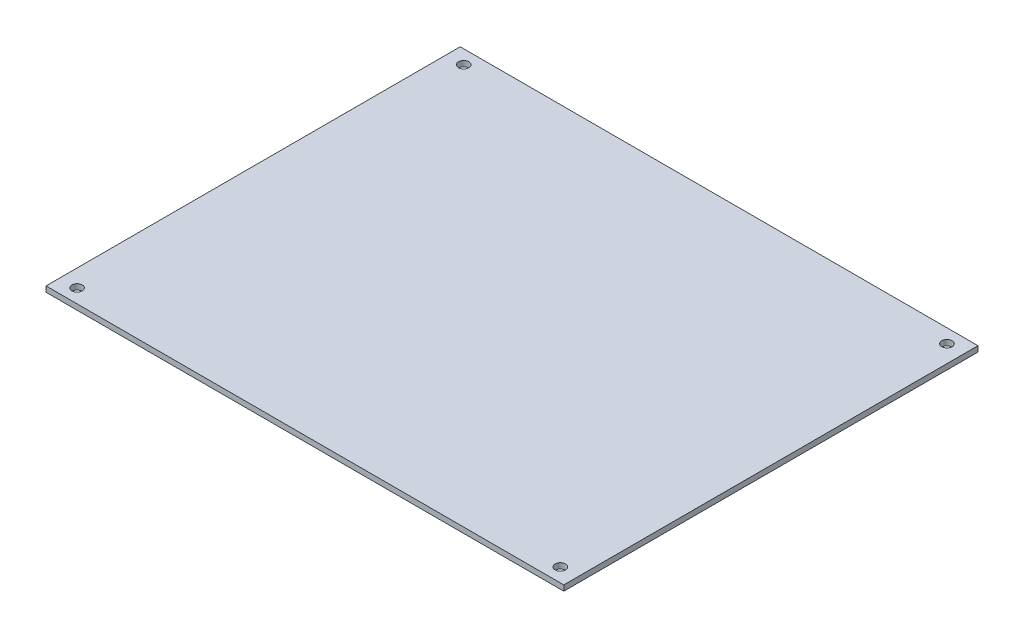
SolidWorks part; units mm, degrees
ref_plane "前视基准面" through (0, 0, 0) normal (0, 0, 1) x (1, 0, 0)
ref_plane "上视基准面" through (0, 0, 0) normal (0, 1, 0) x (1, 0, 0)
ref_plane "右视基准面" through (0, 0, 0) normal (1, 0, 0) x (0, 0, -1)
sketch "Sketch1" plane through (0, 0, 0) normal (0, 1, 0) x (1, 0, 0)
  line L0 (0, 0) -> (0, 28.7732) construction
  line L1 (-75, 60) -> (75, 60)
  line L2 (-75, 60) -> (-75, -60)
  line L3 (-75, -60) -> (75, -60)
  line L4 (75, 60) -> (75, -60)
  line L5 (-75, 60) -> (75, -60) construction
  line L6 (-75, -60) -> (75, 60) construction
  circle A0 centre (70, 56) radius 1.5
  circle A1 centre (70, -56) radius 1.5
  circle A2 centre (-70, -56) radius 1.5
  circle A3 centre (-70, 56) radius 1.5
  point P0 (0, 0)
  dimension "D3" = 3
  dimension "D5" = 3
  dimension "D6" = 5
  dimension "D1" = 150
  dimension "D2" = 120
  dimension "D4" = 5
extrude "Boss-Extrude1" add sketch "Sketch1" along normal blind 1.6
